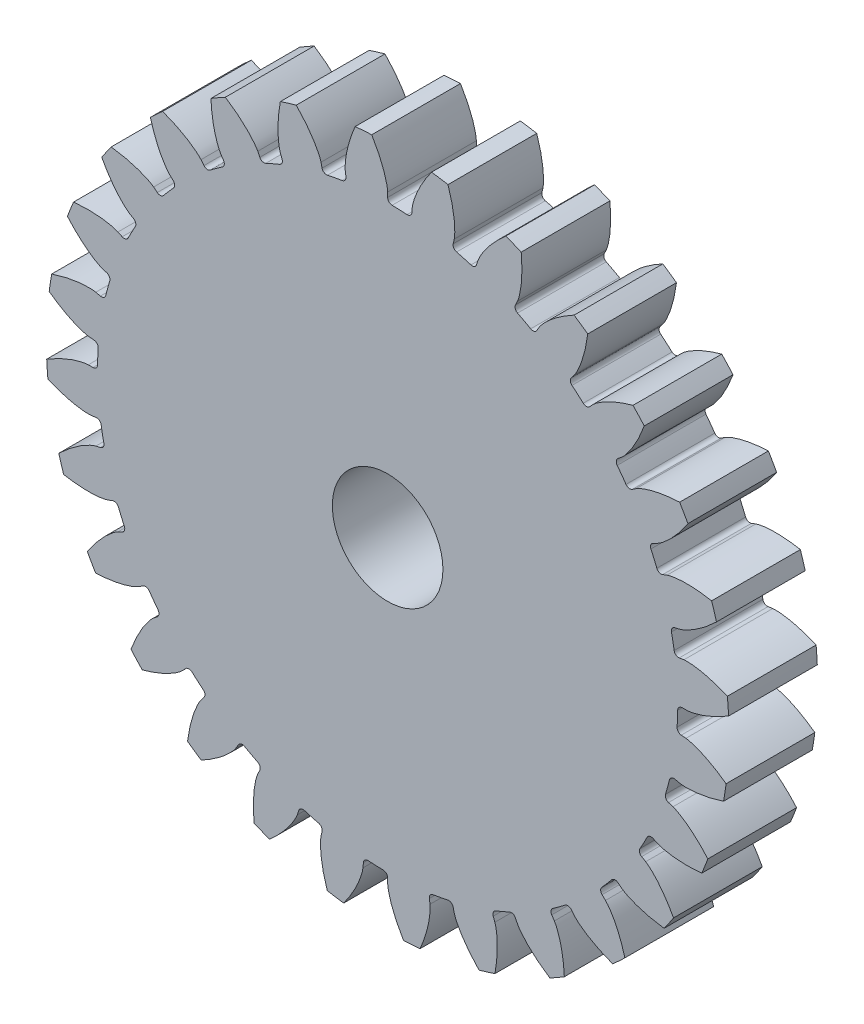
SolidWorks part; units mm, degrees
material "AISI 1020"
ref_plane "Front Plane" through (0, 0, 0) normal (0, 0, 1) x (1, 0, 0)
ref_plane "Top Plane" through (0, 0, 0) normal (0, 1, 0) x (1, 0, 0)
ref_plane "Right Plane" through (0, 0, 0) normal (1, 0, 0) x (0, 0, -1)
sketch "Sketch3" plane through (0, 0, 0) normal (0, 0, 1) x (1, 0, 0)
  circle A0 centre (0, 0) radius 7.5
  dimension "D1" = 15
extrude "Boss-Extrude1" add sketch "Sketch3" along normal blind 1.95 contours A0
sketch "Sketch4" plane through (0, 0, 0) normal (0, 0, 1) x (1, 0, 0)
  line L0 (6.375, 0) -> (6.5778, 0)
  line L1 (0, 0) -> (-7.4936, 0.3089) construction
  line L2 (6.3534, -0.5246) -> (6.5555, -0.5413)
  circle A0 centre (0, 0) radius 7 construction
  circle A1 centre (0, 0) radius 6.5778 construction
  arc A2 (6.3534, -0.5246) -> (6.375, 0) centre (0, 0) ccw
  circle A3 centre (0, 0) radius 7.5 construction
  spline S0 degree 4 poles (6.5778, 0) (6.5801, 0) (6.5864, 0.0002) (6.6059, 0.0015) (6.6442, 0.0057) (6.6913, 0.0136) (6.7452, 0.0251) (6.7969, 0.0381) (6.841, 0.0505) (6.8848, 0.064) (6.9282, 0.0784) (6.9806, 0.097) (7.0431, 0.121) (7.1156, 0.1514) (7.1971, 0.1886) (7.2794, 0.2296) (7.3598, 0.2723) (7.4401, 0.3182) (7.5172, 0.3646) (7.5964, 0.4155) (7.669, 0.464) (7.7493, 0.5213) (7.8137, 0.5685) (7.8975, 0.6339) (7.9466, 0.6735) (8.0036, 0.7209) (8.0287, 0.7425) (8.0441, 0.7558) knots 0 0 0 0 0 0.005377 0.015084 0.04661 0.092111 0.119476 0.146842 0.174209 0.201575 0.228941 0.256307 0.307035 0.361767 0.4165 0.471232 0.525964 0.580697 0.635429 0.690161 0.744894 0.799626 0.854358 0.909091 0.954545 1 1 1 1 1 construction
  spline S1 degree 4 poles (6.5778, 0) (6.5801, 0) (6.5864, 0.0002) (6.6059, 0.0015) (6.6442, 0.0057) (6.6913, 0.0136) (6.7452, 0.0251) (6.7969, 0.0381) (6.841, 0.0505) (6.8848, 0.064) (6.9282, 0.0784) (6.9806, 0.097) (7.0431, 0.121) (7.1156, 0.1514) (7.1971, 0.1886) (7.2794, 0.2296) (7.3598, 0.2723) (7.4401, 0.3182) (7.5172, 0.3646) (7.5964, 0.4155) (7.669, 0.464) (7.7493, 0.5213) (7.8137, 0.5685) (7.8793, 0.6197) (7.9111, 0.645) (7.9273, 0.6581) knots 0 0 0 0 0 0.005377 0.015084 0.04661 0.092111 0.119476 0.146842 0.174209 0.201575 0.228941 0.256307 0.307035 0.361767 0.4165 0.471232 0.525964 0.580697 0.635429 0.690161 0.744894 0.799626 0.854358 0.909091 0.909091 0.909091 0.909091 0.909091
  spline S2 degree 4 poles (106.284, -15.4902) (106.3203, -15.496) (106.4217, -15.5139) (106.6124, -15.5542) (106.9218, -15.6289) (107.4928, -15.787) (108.3484, -16.0665) (109.2774, -16.4238) (110.2481, -16.846) (111.0925, -17.2464) (111.7606, -17.5817) (112.5627, -18.0056) (113.5166, -18.5412) (114.6147, -19.2012) (115.8472, -19.9983) (117.0769, -20.8493) (118.2809, -21.7356) (119.4604, -22.6553) (120.4702, -23.4858) (121.322, -24.2171) (122.1596, -24.9594) (122.8519, -25.5935) (123.5262, -26.2293) (124.2037, -26.8891) (124.7206, -27.4019) (125.2693, -27.9609) (125.7445, -28.4521) (126.1894, -28.925) (126.4234, -29.1763) (126.5387, -29.301) knots 0 0 0 0 0 0.005377 0.015084 0.028532 0.04661 0.092111 0.146842 0.174209 0.201575 0.228941 0.256307 0.307035 0.361767 0.4165 0.471232 0.525964 0.580697 0.635429 0.662795 0.690161 0.744894 0.77226 0.799626 0.826992 0.854358 0.881725 0.909091 0.909091 0.909091 0.909091 0.909091
  spline S3 degree 4 poles (6.5555, -0.5413) (6.5578, -0.5416) (6.564, -0.5423) (6.5833, -0.5451) (6.6212, -0.5525) (6.6674, -0.5642) (6.7202, -0.5801) (6.7707, -0.5974) (6.8136, -0.6133) (6.8562, -0.6303) (6.8983, -0.6483) (6.9489, -0.6712) (7.0092, -0.7002) (7.079, -0.7365) (7.1572, -0.7803) (7.2358, -0.8279) (7.3124, -0.8771) (7.3887, -0.9294) (7.4617, -0.982) (7.5365, -1.0393) (7.6048, -1.0936) (7.6801, -1.1573) (7.7405, -1.2096) (7.8016, -1.266) (7.8312, -1.2939) (7.8463, -1.3082) knots 0 0 0 0 0 0.005377 0.015084 0.04661 0.092111 0.119476 0.146842 0.174209 0.201575 0.228941 0.256307 0.307035 0.361767 0.4165 0.471232 0.525964 0.580697 0.635429 0.690161 0.744894 0.799626 0.854358 0.909091 0.909091 0.909091 0.909091 0.909091
  dimension "D1" = 14
  dimension "D2" = 13.1557
  dimension "D3" = 12.75
  dimension "D4" = 2.36
sketch "Sketch5" plane through (0, 0, 0) normal (0, 0, -1) x (-1, 0, 0)
sketch "Sketch6" plane through (0, 0, 1.95) normal (0, 0, 1) x (1, 0, 0)
  spline S0 degree 4 poles (6.5342, -0.5399) (6.5349, -0.5398) (6.536, -0.5396) (6.5437, -0.5401) (6.5537, -0.541) (6.571, -0.5434) (6.6036, -0.5492) (6.641, -0.558) (6.6914, -0.5715) (6.7442, -0.5885) (6.8022, -0.6092) (6.8629, -0.6334) (6.9373, -0.6658) (7.0237, -0.7075) (7.1221, -0.7603) (7.2266, -0.8222) (7.3293, -0.8887) (7.4285, -0.9579) (7.5269, -1.0321) (7.6204, -1.1066) (7.7156, -1.1885) (7.8017, -1.2656) (7.8967, -1.3575) (7.9709, -1.4312) (8.0677, -1.535) (8.1209, -1.5941) (8.1822, -1.6648) (8.2101, -1.6981) (8.2253, -1.7163) knots 0 0 0 0 0 0.001532 0.003828 0.010321 0.021815 0.038974 0.059764 0.088769 0.117775 0.14678 0.175785 0.213907 0.271917 0.329928 0.387938 0.445948 0.503958 0.561968 0.619978 0.677988 0.735999 0.794009 0.852019 0.910029 0.955015 1 1 1 1 1 construction
  spline S1 degree 4 poles (6.5555, -0.5413) (6.5609, -0.542) (6.5748, -0.5441) (6.6036, -0.5492) (6.641, -0.558) (6.6914, -0.5715) (6.7442, -0.5885) (6.8022, -0.6092) (6.8629, -0.6334) (6.9373, -0.6658) (7.0237, -0.7075) (7.1221, -0.7603) (7.2266, -0.8222) (7.3293, -0.8887) (7.4285, -0.9579) (7.5269, -1.0321) (7.6204, -1.1066) (7.7156, -1.1885) (7.8017, -1.2656) (7.8967, -1.3575) (7.9709, -1.4312) (8.0478, -1.5137) (8.0837, -1.553) (8.102, -1.5735) knots 0.010321 0.010321 0.010321 0.010321 0.010321 0.021815 0.038974 0.059764 0.088769 0.117775 0.14678 0.175785 0.213907 0.271917 0.329928 0.387938 0.445948 0.503958 0.561968 0.619978 0.677988 0.735999 0.794009 0.852019 0.910029 0.910029 0.910029 0.910029 0.910029
sketch "Sketch7" plane through (0, 0, 0) normal (0, 0, -1) x (-1, 0, 0)
extrude "Cut-Extrude1" cut sketch "Sketch4" against normal through all and the other way through all contours S3 L2 A2 L0 S1
pattern_circular "CirPattern1" count 28 over 360 about axis through (0, 0, 1.95) along (0, 0, 1) of "Cut-Extrude1"
fillet "Fillet1" radius 0.1 56 edges at (6.2152, -1.4186, 0.975) (6.0773, -1.9253, 0.975) (5.7437, -2.766, 0.975) (5.4966, -3.2293, 0.975) (3.2293, 5.4966, 0.975) (3.9747, 4.9842, 0.975) (4.3715, 4.6402, 0.975) (4.9842, 3.9747, 0.975) (5.2944, 3.5511, 0.975) (5.7437, 2.766, 0.975) (5.9518, 2.2839, 0.975) (6.2152, 1.4186, 0.975) (6.3108, 0.9023, 0.975) (6.375, 0, 0.975) (6.3534, -0.5246, 0.975) (4.9842, -3.9747, 0.975) (3.9747, -4.9842, 0.975) (4.6402, -4.3715, 0.975) (3.5511, -5.2944, 0.975) (2.766, -5.7437, 0.975) (2.2839, -5.9518, 0.975) (1.4186, -6.2152, 0.975) (0.9023, -6.3108, 0.975) (0, -6.375, 0.975) (-0.5246, -6.3534, 0.975) (-2.766, -5.7437, 0.975) (-1.4186, -6.2152, 0.975) (-1.9253, -6.0773, 0.975) (-3.2293, -5.4966, 0.975) (-3.9747, -4.9842, 0.975) (-4.3715, -4.6402, 0.975) (-4.9842, -3.9747, 0.975) (-5.2944, -3.5511, 0.975) (-5.7437, -2.766, 0.975) (-6.2152, -1.4186, 0.975) (-5.9518, -2.2839, 0.975) (-6.375, 0, 0.975) (-6.3108, -0.9023, 0.975) (-6.3534, 0.5246, 0.975) (-6.2152, 1.4186, 0.975) (-6.0773, 1.9253, 0.975) (-5.7437, 2.766, 0.975) (-5.4966, 3.2293, 0.975) (-4.9842, 3.9747, 0.975) (-4.6402, 4.3715, 0.975) (-3.9747, 4.9842, 0.975) (-3.5511, 5.2944, 0.975) (-2.766, 5.7437, 0.975) (-2.2839, 5.9518, 0.975) (-1.4186, 6.2152, 0.975) (-0.9023, 6.3108, 0.975) (0, 6.375, 0.975) (0.5246, 6.3534, 0.975) (1.4186, 6.2152, 0.975) (1.9253, 6.0773, 0.975) (2.766, 5.7437, 0.975)
sketch "Sketch8" plane through (0, 0, 1.95) normal (0, 0, 1) x (1, 0, 0)
  circle A0 centre (0, 0) radius 1.215
extrude "Cut-Extrude2" cut sketch "Sketch8" against normal through all
sketch "Sketch9" plane through (0, 0, 0) normal (0, 0, -1) x (-1, 0, 0)
  circle A0 centre (0, 0) radius 7
equation "\"P\"= 2'Diametral Pitch"
equation "\"N\"= 28'Numver of teeth"
equation "\"phi\"= 20deg'Pressure Angle"
equation "\"a\"= 1 / \"P\"'Addendum"
equation "\"b\"= 1.25 / \"P\"'Dedendun"
equation "\"c\"= \"b\" - \"a\"'clearance"
equation "\"dp\"= \"N\" / \"P\"'pitch circle diameter"
equation "\"db\"= \"dp\" * cos ( \"phi\" )'base circle diameter"
equation "\"D1@Sketch3\"= \"dp\" + 2 * \"a\""
equation "\"D1@Sketch4\"= \"dp\"'Pitch circle diametr"
equation "\"D2@Sketch4\"= \"db\"'Base Circle"
equation "\"D3@Sketch4\"= \"dp\" - 2 * \"b\""
equation "\"alpha\"= sqr ( \"dp\" ^ 2 - \"db\" ^ 2 ) / \"db\" * 180 / pi - \"phi\""
equation "\"Beta\"= ( 360 / ( 4 * \"N\" ) - \"alpha\" ) * 2"
equation "\"D4@Sketch4\"= 360 / ( 4 * \"N\" ) - \"alpha\""
